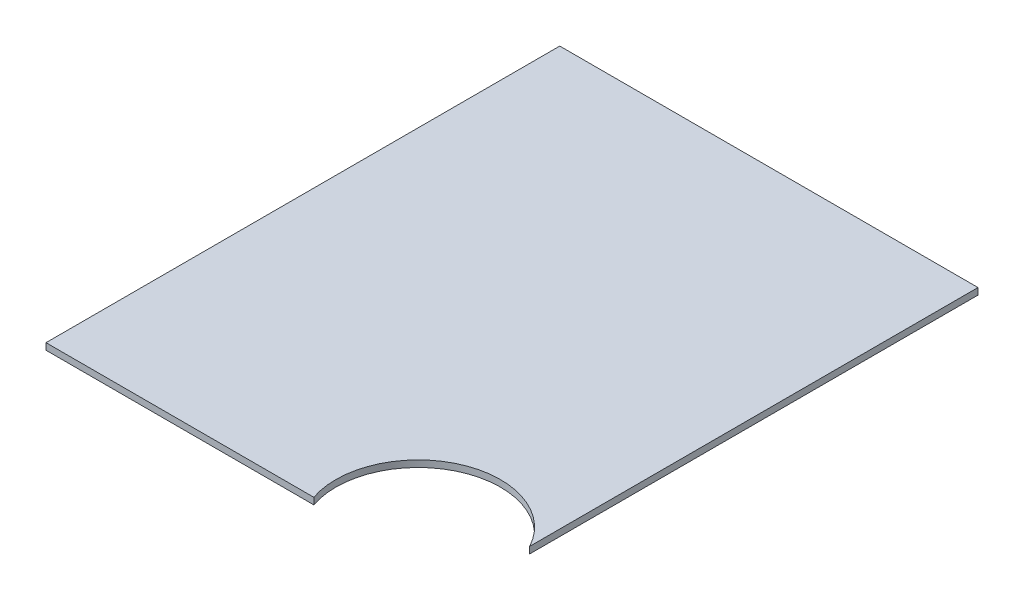
SolidWorks part; units mm, degrees
ref_plane "Front Plane" through (0, 0, 0) normal (0, 0, 1) x (1, 0, 0)
ref_plane "Top Plane" through (0, 0, 0) normal (0, 1, 0) x (1, 0, 0)
ref_plane "Right Plane" through (0, 0, 0) normal (1, 0, 0) x (0, 0, -1)
sketch "Sketch1" plane through (0, 0, 0) normal (0, 1, 0) x (1, 0, 0)
  line L1 (63.5, -78) -> (-63.5, -78)
  line L2 (63.5, -78) -> (63.5, 78)
  line L3 (63.5, 78) -> (-63.5, 78)
  line L4 (-63.5, -78) -> (-63.5, 78)
  line L5 (63.5, -78) -> (-63.5, 78) construction
  line L6 (63.5, 78) -> (-63.5, -78) construction
  point P0 (0, 0)
  dimension "D1" = 156
  dimension "D2" = 127
extrude "Boss-Extrude1" add sketch "Sketch1" along normal blind 2
ref_plane "Plane1" through (0, 2, 0) normal (0, 1, 0) x (1, 0, 0)
sketch "Sketch2" plane through (0, 2, 0) normal (0, 1, 0) x (1, 0, 0)
  line L0 (-63.5, -78) -> (-41.5, -78) construction
  line L1 (0, 0) -> (0, -47.1792) construction
  line L2 (-63.5, -78) -> (63.5, -78) construction
  line L6 (-41.5, -78) -> (-41.5, -70) construction
  circle A2 centre (41.5, -70) radius 25
  dimension "D1" = 22
  dimension "D2" = 8
extrude "Cut-Extrude1" cut sketch "Sketch2" against normal blind 2
